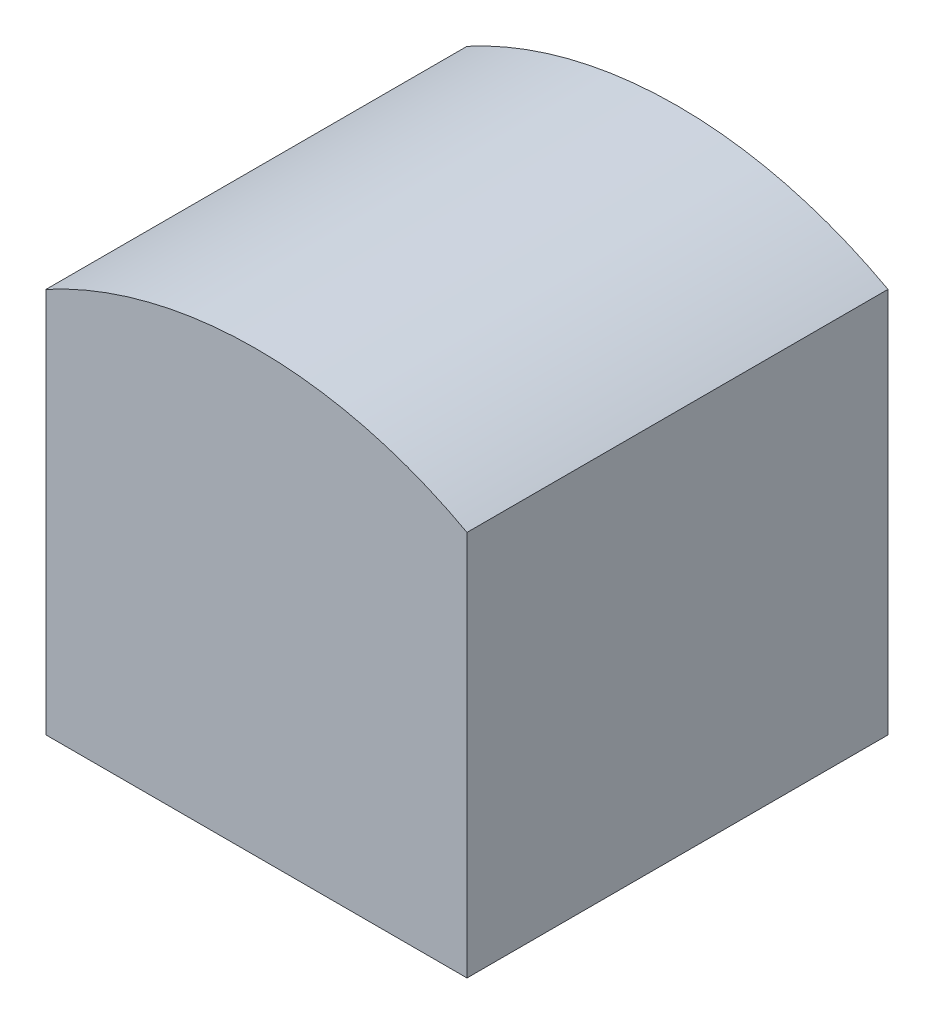
SolidWorks part; units mm, degrees
ref_plane "Front Plane" through (0, 0, 0) normal (0, 0, 1) x (1, 0, 0)
ref_plane "Top Plane" through (0, 0, 0) normal (0, 1, 0) x (1, 0, 0)
ref_plane "Right Plane" through (0, 0, 0) normal (1, 0, 0) x (0, 0, -1)
sketch "Sketch1" plane through (0, 0, 0) normal (0, 0, 1) x (1, 0, 0)
  line L5 (60, -55) -> (-60, -55)
  line L6 (60, -55) -> (60, 55)
  line L8 (-60, -55) -> (-60, 55)
  arc A0 (60, 55) -> (-60, 55) centre (0, -55) ccw
  point P5 (60, 0)
  dimension "D1" = 120
  dimension "D2" = 110
  dimension "D3" = 60
extrude "Boss-Extrude1" add sketch "Sketch1" along normal blind 120
